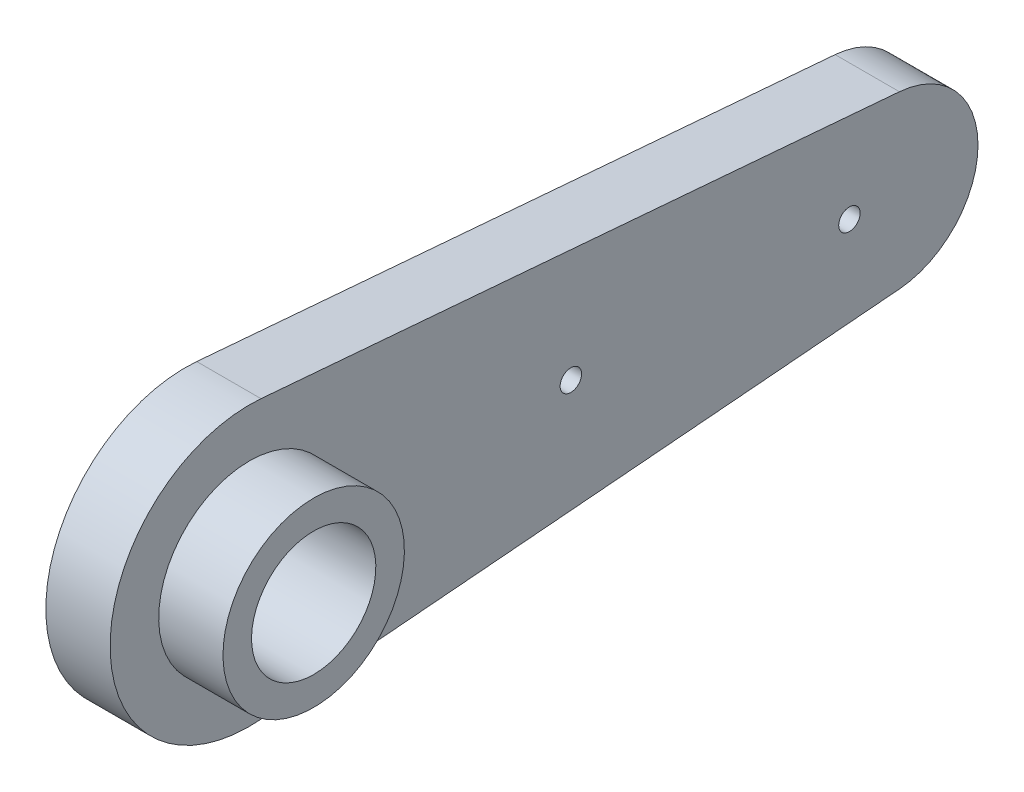
SolidWorks part; units mm, degrees
ref_plane "Plan de face" through (0, 0, 0) normal (0, 0, 1) x (1, 0, 0)
ref_plane "Plan de dessus" through (0, 0, 0) normal (0, 1, 0) x (1, 0, 0)
ref_plane "Plan de droite" through (0, 0, 0) normal (1, 0, 0) x (0, 0, -1)
sketch "Esquisse1" plane through (51.2, 0, 0) normal (-1, 0, 0) x (0, 0, 1)
  line L0 (-16.4191, -63.9) -> (-46.4191, -63.9) construction
  line L1 (-16.4191, -63.9) -> (-51.4191, -63.9) construction
  line L2 (-16.9607, -57.4226) -> (-46.7524, -59.9139)
  line L3 (-16.9607, -70.3774) -> (-46.7524, -67.8861)
  circle A0 centre (-16.4191, -63.9) radius 2.9
  arc A1 (-16.9607, -70.3774) -> (-16.9607, -57.4226) centre (-16.4191, -63.9) ccw
  circle A2 centre (-16.4191, -63.9) radius 2.9 construction
  arc A3 (-46.7524, -59.9139) -> (-46.7524, -67.8861) centre (-46.4191, -63.9) ccw
  circle A4 centre (-31.4191, -63.9) radius 0.5
  circle A5 centre (-44.4191, -63.9) radius 0.5
  dimension "D1" = 13
  dimension "D2" = 8
  dimension "D4" = 1
  dimension "D3" = 30
  dimension "D5" = 15
  dimension "D6" = 28
extrude "Boss.-Extru.1" add sketch "Esquisse1" along normal blind 6
sketch "Esquisse2" plane through (51.2, 0, 0) normal (1, 0, 0) x (0, 0, -1)
  line L2 (16.9607, -70.3774) -> (46.7524, -67.8861)
  line L3 (46.7524, -59.9139) -> (16.9607, -57.4226)
  line L4 (16.9607, -70.3774) -> (46.7524, -67.8861)
  line L5 (46.7524, -59.9139) -> (16.9607, -57.4226)
  circle A0 centre (16.4191, -63.9) radius 4.233
  arc A2 (16.9607, -57.4226) -> (16.9607, -70.3774) centre (16.4191, -63.9) ccw
  arc A3 (46.7524, -67.8861) -> (46.7524, -59.9139) centre (46.4191, -63.9) ccw
  arc A4 (16.9607, -57.4226) -> (16.9607, -70.3774) centre (16.4191, -63.9) ccw
  arc A5 (46.7524, -67.8861) -> (46.7524, -59.9139) centre (46.4191, -63.9) ccw
  dimension "D1" = 0
extrude "Enlèv. mat.-Extru.1" cut sketch "Esquisse2" against normal blind 3
